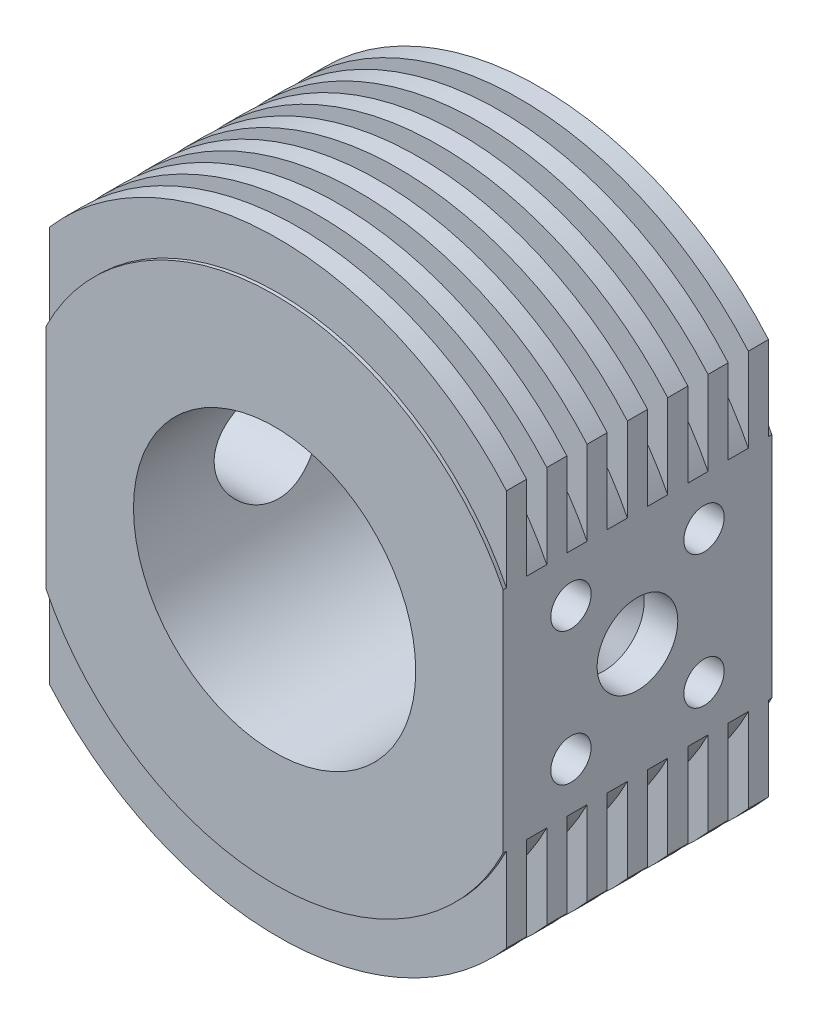
SolidWorks part; units mm, degrees
ref_plane "Front Plane" through (0, 0, 0) normal (0, 0, 1) x (1, 0, 0)
ref_plane "Top Plane" through (0, 0, 0) normal (0, 1, 0) x (1, 0, 0)
ref_plane "Right Plane" through (0, 0, 0) normal (1, 0, 0) x (0, 0, -1)
sketch "Sketch2" plane through (0, 0, 0) normal (0, 0, 1) x (1, 0, 0)
  line L2 (-17, 14.7394) -> (-17, -14.7394)
  line L4 (17, 14.7394) -> (17, -14.7394)
  line L5 (-17, 30.4521) -> (17, -30.4521) construction
  line L6 (-17, -30.4521) -> (17, 30.4521) construction
  circle A0 centre (0, 0) radius 10.5
  arc A1 (-17, -14.7394) -> (17, -14.7394) centre (0, 0) ccw
  arc A2 (17, 14.7394) -> (-17, 14.7394) centre (0, 0) ccw
  dimension "D1" = 45
  dimension "D2" = 21
  dimension "D3" = 34
extrude "Boss-Extrude1" add sketch "Sketch2" along normal blind 20
sketch "Sketch3" plane through (0, 0, 0) normal (0, 0, -1) x (-1, 0, 0)
  circle A0 centre (0, 0) radius 12
  dimension "D1" = 24
extrude "Cut-Extrude1" cut sketch "Sketch3" against normal blind 3
sketch "Sketch4" plane through (0, 0, 20) normal (0, 0, 1) x (1, 0, 0)
  circle A0 centre (0, 0) radius 19
  dimension "D1" = 38
extrude "Cut-Extrude2" cut sketch "Sketch4" against normal blind 0.25 flip side to cut
sketch "Sketch5" plane through (0, 0, 0) normal (0, 0, -1) x (-1, 0, 0)
  circle A0 centre (0, 0) radius 19
  dimension "D1" = 38
extrude "Cut-Extrude3" cut sketch "Sketch5" against normal blind 0.25 flip side to cut
ref_plane "Plane1" through (0, 0, 18.25) normal (0, 0, 1) x (1, 0, 0)
sketch "Sketch8" plane through (0, 0, 18.25) normal (0, 0, 1) x (1, 0, 0)
  line L0 (17, 8.4853) -> (17, 14.7394) construction
  line L1 (17, 8.4853) -> (17, 14.7394)
  line L2 (-17, 14.7394) -> (-17, 8.4853) construction
  line L3 (-17, 14.7394) -> (-17, 8.4853)
  arc A0 (17, 14.7394) -> (-17, 14.7394) centre (0, 0) ccw construction
  arc A1 (17, 8.4853) -> (-17, 8.4853) centre (0, 0) ccw construction
  arc A2 (17, 8.4853) -> (-17, 8.4853) centre (0, 0) ccw
  arc A3 (17, 14.7394) -> (-17, 14.7394) centre (0, 0) ccw
extrude "Cut-Extrude4" cut sketch "Sketch8" against normal blind 1.5
pattern_linear "LPattern1" count 6 spacing 3 along (0, 0, -1) of "Cut-Extrude4"
mirror "Mirror3" about plane through (0, 0, 0) normal (0, 1, 0) of "LPattern1", "Cut-Extrude4"
sketch "Sketch10" plane through (-17, 0, 0) normal (-1, 0, 0) x (0, 0, 1)
  line L0 (0, 8.4853) -> (0, -8.4853) construction
  circle A0 centre (10, 0) radius 4
  dimension "D1" = 8
  dimension "D2" = 10
extrude "Cut-Extrude5" cut sketch "Sketch10" against normal blind 9.5
sketch "Sketch11" plane through (-17, 0, 0) normal (-1, 0, 0) x (0, 0, 1)
  line L0 (10, 0) -> (3, 0) construction
  line L1 (10, 0) -> (5.0503, 4.9497) construction
  circle A0 centre (10, 0) radius 7 construction
  circle A1 centre (5.0503, 4.9497) radius 1.5
  circle A2 centre (5.0503, -4.9497) radius 1.5
  circle A3 centre (14.9497, -4.9497) radius 1.5
  circle A4 centre (14.9497, 4.9497) radius 1.5
  point P15 (10, 0)
  dimension "D2" = 3
  dimension "D4" = 14
  dimension "D1" = 45
  dimension "D3" = 4
extrude "Cut-Extrude6" cut sketch "Sketch11" against normal blind 4
ref_plane "Plane2" through (0, 0, 10) normal (0, 0, -1) x (-1, 0, 0)
sketch "Sketch14" plane through (0, 0, 10) normal (0, 0, -1) x (-1, 0, 0)
  line L0 (-17, 0) -> (-11.5, 0)
  line L1 (-17, -8.4853) -> (-17, 8.4853) construction
  line L2 (-11.5, 0) -> (-14.5, -3)
  line L3 (-14.5, -3) -> (-17, -3)
  line L4 (-17, -3) -> (-17, 0)
  dimension "D1" = 3
  dimension "D2" = 2.5
  dimension "D3" = 45
revolve "Cut-Revolve1" cut sketch "Sketch14" angle 360 about L0
mirror "Mirror4" about plane through (0, 0, 0) normal (1, 0, 0) of "Cut-Extrude6"
